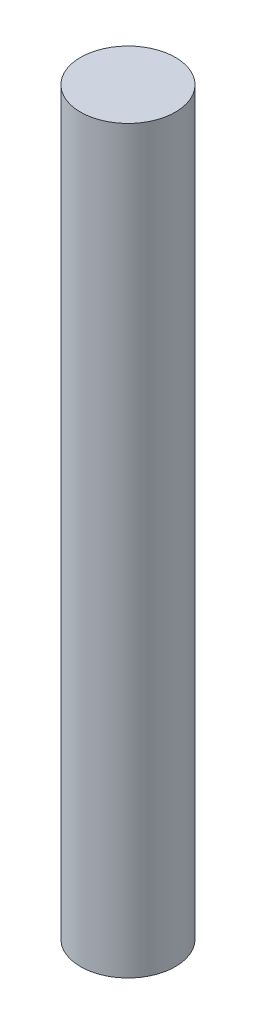
SolidWorks part; units mm, degrees
ref_plane "Front Plane" through (0, 0, 0) normal (0, 0, 1) x (1, 0, 0)
ref_plane "Top Plane" through (0, 0, 0) normal (0, 1, 0) x (1, 0, 0)
ref_plane "Right Plane" through (0, 0, 0) normal (1, 0, 0) x (0, 0, -1)
sketch "Sketch1" plane through (0, 0, 0) normal (0, 1, 0) x (1, 0, 0)
  circle A0 centre (0, 0) radius 1.5875
  dimension "D1" = 3.175
extrude "Boss-Extrude1" add sketch "Sketch1" along normal blind 24.765
